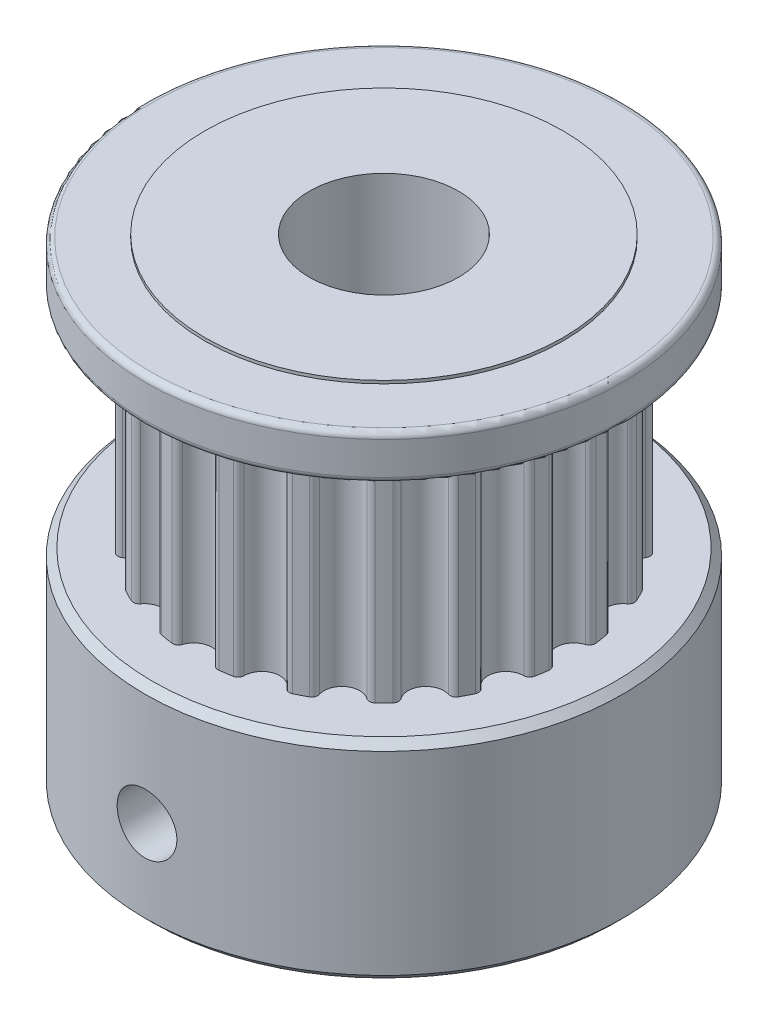
SolidWorks part; units mm, degrees
ref_plane "Front Plane" through (0, 0, 0) normal (0, 0, 1) x (1, 0, 0)
ref_plane "Top Plane" through (0, 0, 0) normal (0, 1, 0) x (1, 0, 0)
ref_plane "Right Plane" through (0, 0, 0) normal (1, 0, 0) x (0, 0, -1)
sketch "Sketch1" plane through (0, 0, 0) normal (0, 1, 0) x (1, 0, 0)
  circle A0 centre (0, 0) radius 8
  dimension "D1" = 16
extrude "Boss-Extrude1" add sketch "Sketch1" along normal blind 7
sketch "Sketch2" plane through (0, 7, 0) normal (0, 1, 0) x (1, 0, 0)
  circle A0 centre (0, 0) radius 6.365
  dimension "D1" = 12.73
extrude "Boss-Extrude2" add sketch "Sketch2" along normal blind 7.5
sketch "Sketch4" plane through (0, 14.5, 0) normal (0, 1, 0) x (1, 0, 0)
  circle A0 centre (0, 6.365) radius 0.6
  circle A1 centre (0, 0) radius 6.365 construction
  dimension "D1" = 1.2
extrude "Cut-Extrude1" cut sketch "Sketch4" against normal up to surface (7.5 mm away) up to face at (0, 7, 6.365)
fillet "Fillet1" radius 0.2 2 edges at (0.5993, 10.75, -6.3367) (-0.5993, 10.75, -6.3367)
pattern_circular "CirPattern1" count 20 over 360 about axis through (0, 0, 0) along (0, 1, 0) of "Cut-Extrude1", "Fillet1"
sketch "Sketch3" plane through (0, 14.5, 0) normal (0, 1, 0) x (1, 0, 0)
  circle A0 centre (0, 0) radius 8
  dimension "D1" = 16
extrude "Boss-Extrude3" add sketch "Sketch3" along normal blind 1.5
sketch "Sketch5" plane through (0, 16, 0) normal (0, 1, 0) x (1, 0, 0)
  circle A0 centre (0, 0) radius 6
  dimension "D1" = 12
extrude "Boss-Extrude4" add sketch "Sketch5" along normal blind 0.1
sketch "Sketch7" plane through (0, 0, 0) normal (0, 1, 0) x (1, 0, 0)
  circle A0 centre (0, 0) radius 2.5
  dimension "D1" = 5
extrude "Cut-Extrude2" cut sketch "Sketch7" along normal blind 20.1
chamfer "Chamfer1" distance 0.25 angle 45 2 edges at (0, 0, 8) (0, 7, 8)
fillet "Fillet2" radius 0.2 2 edges at (0, 14.5, 8) (0, 16, 8)
ref_plane "Plane1" through (0, 0, 8) normal (0, 0, 1) x (1, 0, 0)
sketch "Sketch9" plane through (0, 0, 8) normal (0, 0, 1) x (1, 0, 0)
  circle A0 centre (0, 3) radius 1
  dimension "D1" = 2
  dimension "D2" = 3
extrude "Cut-Extrude3" cut sketch "Sketch9" against normal blind 7.1
pattern_circular "CirPattern2" count 2 every 90 about axis through (0, 7, 0) along (0, -1, 0) of "Cut-Extrude3"
